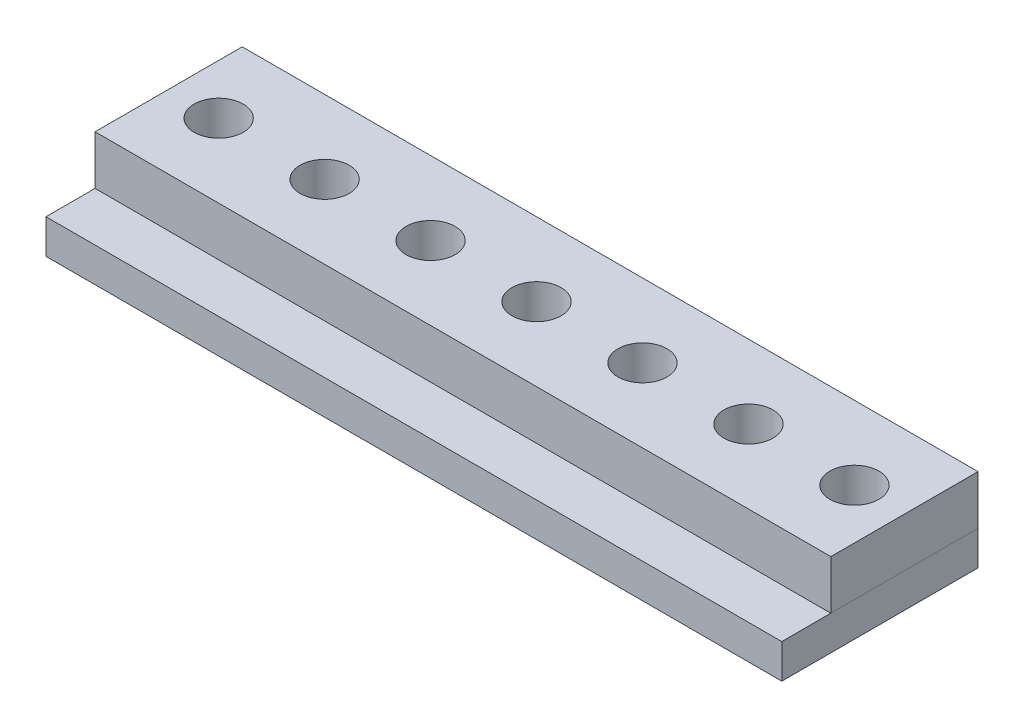
SolidWorks part; units mm, degrees
ref_plane "Front Plane" through (0, 0, 0) normal (0, 0, 1) x (1, 0, 0)
ref_plane "Top Plane" through (0, 0, 0) normal (0, 1, 0) x (1, 0, 0)
ref_plane "Right Plane" through (0, 0, 0) normal (1, 0, 0) x (0, 0, -1)
sketch "Sketch1" plane through (0, 0, 0) normal (0, 1, 0) x (1, 0, 0)
  line L0 (-750, 0) -> (-648, 0) construction
  line L1 (-750, -150) -> (750, -150)
  line L2 (-750, -150) -> (-750, 150)
  line L3 (-750, 150) -> (750, 150)
  line L4 (750, -150) -> (750, 150)
  line L5 (-750, -150) -> (750, 150) construction
  line L6 (-750, 150) -> (750, -150) construction
  circle A0 centre (-648, 0) radius 50
  circle A1 centre (-432, 0) radius 50
  circle A2 centre (-216, 0) radius 50
  circle A3 centre (0, 0) radius 50
  circle A4 centre (216, 0) radius 50
  circle A5 centre (432, 0) radius 50
  circle A6 centre (648, 0) radius 50
  point P0 (0, 0)
  dimension "D4" = 100
  dimension "D1" = 300
  dimension "D2" = 1500
  dimension "D3" = 102
  dimension "D6" = 216
  dimension "D5" = 7
extrude "Boss-Extrude1" add sketch "Sketch1" along normal blind 100
sketch "Sketch2" plane through (0, 0, 0) normal (0, -1, 0) x (1, 0, 0)
  line L1 (-750, -150) -> (750, -150)
  line L2 (-750, -150) -> (-750, 250)
  line L3 (-750, 250) -> (750, 250)
  line L4 (750, -150) -> (750, 250)
  dimension "D1" = 400
extrude "Boss-Extrude3" add sketch "Sketch2" along normal blind 70 separate body
